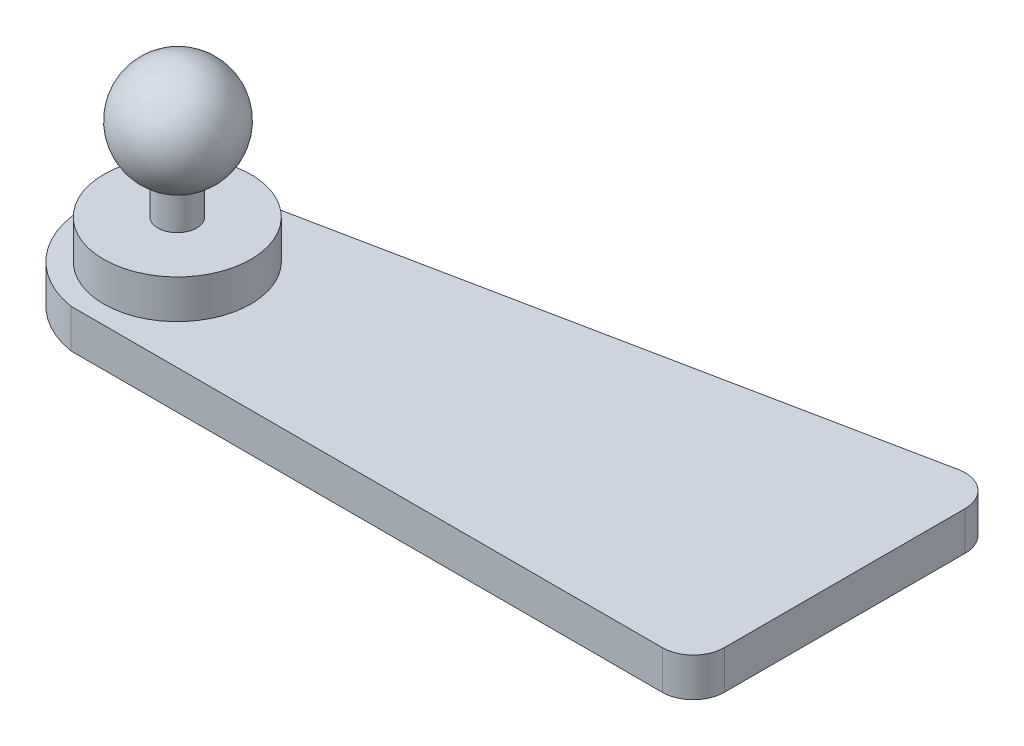
SolidWorks part; units mm, degrees
material "Chrome Stainless Steel"
ref_plane "Front Plane" through (0, 0, 0) normal (0, 0, 1) x (1, 0, 0)
ref_plane "Top Plane" through (0, 0, 0) normal (0, 1, 0) x (1, 0, 0)
ref_plane "Right Plane" through (0, 0, 0) normal (1, 0, 0) x (0, 0, -1)
sketch "Sketch1" plane through (0, 0, 0) normal (0, 1, 0) x (1, 0, 0)
  line L0 (0, 0) -> (51.0268, 0)
  line L1 (51.0268, 0) -> (51.0268, 25.4)
  line L2 (51.0268, 25.4) -> (-0.3214, 14.9944)
  arc A1 (-0.3214, 14.9944) -> (0, 0) centre (1.192, 7.5262) ccw
  dimension "D1" = 49.8348
  dimension "D4" = 25.4
extrude "Boss-Extrude1" add sketch "Sketch1" along normal blind 3.175 contours L2 A1 L0 L1
sketch "Sketch2" plane through (0, 3.175, 0) normal (0, 1, 0) x (1, 0, 0)
  circle A0 centre (1.192, 7.5262) radius 6.0325
  dimension "D1" = 12.065
extrude "Boss-Extrude2" add sketch "Sketch2" along normal blind 3.175
sketch "Sketch3" plane through (0, 6.35, 0) normal (0, 1, 0) x (1, 0, 0)
  circle A0 centre (1.192, 7.5262) radius 1.5875
  dimension "D1" = 3.175
extrude "Boss-Extrude3" add sketch "Sketch3" along normal blind 3.175
sketch "Sketch4" plane through (0, 9.525, 0) normal (0, 1, 0) x (1, 0, 0)
  line L0 (-0.3955, 7.5262) -> (26.2228, 7.5262)
  circle A0 centre (1.192, 7.5262) radius 1.5875 construction
  circle A1 centre (1.192, 7.5262) radius 1.5875 construction
ref_plane "Plane1" through (0, 0, -7.5262) normal (0, 0, 1) x (1, 0, 0)
sketch "Sketch5" plane through (0, 0, -7.5262) normal (0, 0, 1) x (1, 0, 0)
  line L1 (1.251, 17.526) -> (1.251, 8.89)
  line L2 (7.2245, 6.35) -> (-4.8405, 6.35) construction
  arc A1 (1.251, 17.526) -> (1.251, 8.89) centre (1.251, 13.208) ccw
  dimension "D2" = 2.54
revolve "Revolve1" add sketch "Sketch5" angle 360 about L1
fillet "Fillet1" radius 2.54 2 edges at (51.0268, 1.5875, -25.4) (51.0268, 1.5875, 0)
